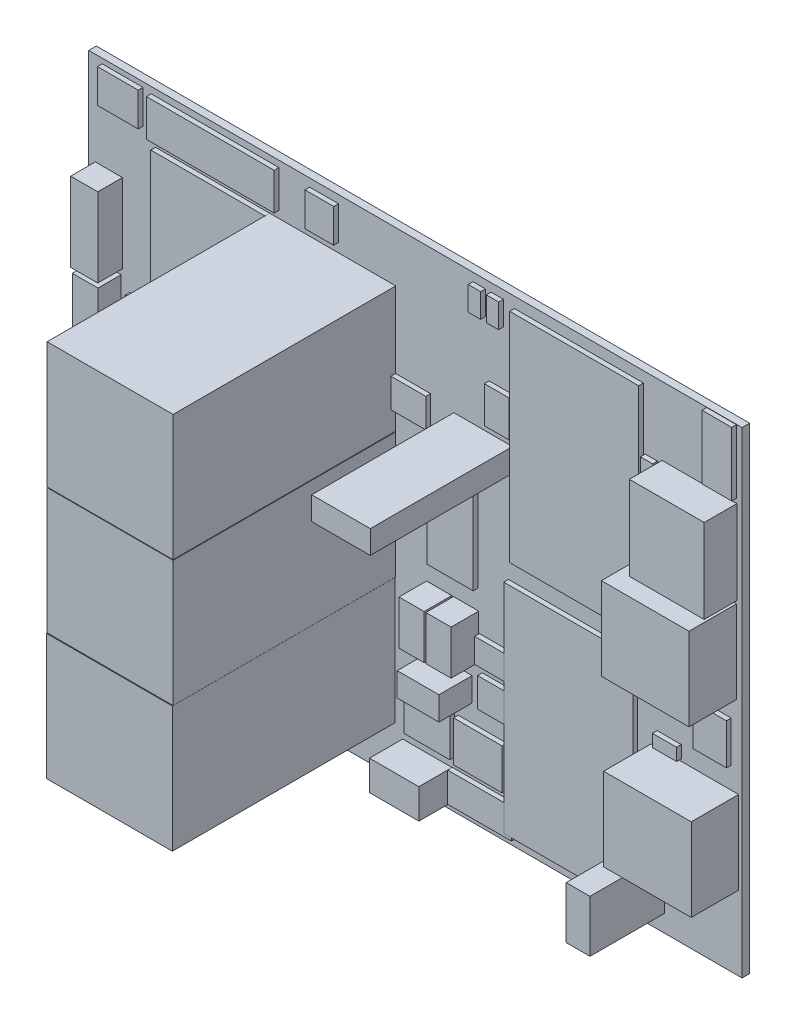
SolidWorks part; units mm, degrees
ref_plane "Plan de face" through (0, 0, 0) normal (0, 0, 1) x (1, 0, 0)
ref_plane "Plan de dessus" through (0, 0, 0) normal (0, 1, 0) x (1, 0, 0)
ref_plane "Plan de droite" through (0, 0, 0) normal (1, 0, 0) x (0, 0, -1)
sketch "Esquisse1" plane through (0, 0, 0) normal (0, 0, 1) x (1, 0, 0)
  line L0 (-2.0638, -0.1588) -> (135.87, -0.1588)
  line L1 (135.87, -0.1588) -> (135.87, 100.4762)
  line L2 (135.87, 100.4762) -> (-2.0638, 100.4762)
  line L3 (-2.0638, 100.4762) -> (-2.0638, -0.1588)
extrude "BOARD" add sketch "Esquisse1" along normal blind 1.6 separate body
ref_plane "Plan1" through (0, 0, 1.6) normal (0, 0, 1) x (1, 0, 0)
sketch "Esquisse2" plane through (0, 0, 0) normal (0, 0, 1) x (1, 0, 0)
  line L0 (109.1238, 29.3513) -> (109.1238, 26.2112)
  line L1 (109.1238, 26.2112) -> (110.9038, 26.2112)
  line L2 (110.9038, 26.2112) -> (110.9038, 29.3513)
  line L3 (110.9038, 29.3513) -> (109.1238, 29.3513)
extrude "CAP_0805-1" add sketch "Esquisse2" against normal blind 1 separate body
sketch "Esquisse3" plane through (0, 0, 0) normal (0, 0, 1) x (1, 0, 0)
  line L0 (110.9038, 22.8775) -> (110.9038, 26.0175)
  line L1 (110.9038, 26.0175) -> (109.1238, 26.0175)
  line L2 (109.1238, 26.0175) -> (109.1238, 22.8775)
  line L3 (109.1238, 22.8775) -> (110.9038, 22.8775)
extrude "CAP_0805-2" add sketch "Esquisse3" against normal blind 1 separate body
sketch "Esquisse4" plane through (0, 0, 0) normal (0, 0, 1) x (1, 0, 0)
  line L0 (94.1562, 24.0337) -> (97.2962, 24.0337)
  line L1 (97.2962, 24.0337) -> (97.2962, 25.8137)
  line L2 (97.2962, 25.8137) -> (94.1562, 25.8137)
  line L3 (94.1562, 25.8137) -> (94.1562, 24.0337)
extrude "CAP_0805-3" add sketch "Esquisse4" against normal blind 1 separate body
sketch "Esquisse5" plane through (0, 0, 0) normal (0, 0, 1) x (1, 0, 0)
  line L0 (94.7913, 37.845) -> (97.9312, 37.845)
  line L1 (97.9312, 37.845) -> (97.9312, 39.625)
  line L2 (97.9312, 39.625) -> (94.7913, 39.625)
  line L3 (94.7913, 39.625) -> (94.7913, 37.845)
extrude "CAP_0805-4" add sketch "Esquisse5" against normal blind 1 separate body
sketch "Esquisse6" plane through (0, 0, 0) normal (0, 0, 1) x (1, 0, 0)
  line L0 (68.0479, 19.7784) -> (68.0479, 15.7816)
  line L1 (68.0479, 15.7816) -> (70.0393, 15.7816)
  line L2 (70.0393, 15.7816) -> (70.0393, 19.7784)
  line L3 (70.0393, 19.7784) -> (68.0479, 19.7784)
extrude "C0805-1" add sketch "Esquisse6" against normal blind 1 separate body
sketch "Esquisse7" plane through (0, 0, 0) normal (0, 0, 1) x (1, 0, 0)
  line L0 (68.0479, 14.3809) -> (68.0479, 10.3841)
  line L1 (68.0479, 10.3841) -> (70.0393, 10.3841)
  line L2 (70.0393, 10.3841) -> (70.0393, 14.3809)
  line L3 (70.0393, 14.3809) -> (68.0479, 14.3809)
extrude "C0805-2" add sketch "Esquisse7" against normal blind 1 separate body
sketch "Esquisse8" plane through (0, 0, 1.6) normal (0, 0, 1) x (1, 0, 0)
  line L0 (36.15, 63.1475) -> (62.75, 63.1475)
  line L1 (62.75, 63.1475) -> (62.75, 36.5975)
  line L2 (62.75, 36.5975) -> (36.15, 36.5975)
  line L3 (36.15, 36.5975) -> (36.15, 63.1475)
extrude "SLPX102M200C4P3_47.000000-1" add sketch "Esquisse8" along normal blind 47 separate body
sketch "Esquisse9" plane through (0, 0, 1.6) normal (0, 0, 1) x (1, 0, 0)
  line L0 (36.15, 89.8175) -> (62.75, 89.8175)
  line L1 (62.75, 89.8175) -> (62.75, 63.2675)
  line L2 (62.75, 63.2675) -> (36.15, 63.2675)
  line L3 (36.15, 63.2675) -> (36.15, 89.8175)
extrude "Board_Outline2" add sketch "Esquisse9" along normal blind 47 separate body
sketch "Esquisse10" plane through (0, 0, 1.6) normal (0, 0, 1) x (1, 0, 0)
  line L0 (62.5925, 9.8775) -> (35.9925, 9.8775)
  line L1 (35.9925, 9.8775) -> (35.9925, 36.4275)
  line L2 (35.9925, 36.4275) -> (62.5925, 36.4275)
  line L3 (62.5925, 36.4275) -> (62.5925, 9.8775)
extrude "SLPX102M200C4P3_47.000000-3" add sketch "Esquisse10" along normal blind 47 separate body
sketch "Esquisse11" plane through (0, 0, 1.6) normal (0, 0, 1) x (1, 0, 0)
  line L0 (-0.6375, 52.0425) -> (-0.6375, 62.8925)
  line L1 (-0.6375, 62.8925) -> (4.7875, 62.8925)
  line L2 (4.7875, 62.8925) -> (4.7875, 52.0425)
  line L3 (4.7875, 52.0425) -> (-0.6375, 52.0425)
extrude "TO254P490X1000X2143-3P_4.900000-1" add sketch "Esquisse11" along normal blind 4.9 separate body
sketch "Esquisse12" plane through (0, 0, 1.6) normal (0, 0, 1) x (1, 0, 0)
  line L0 (-0.955, 23.15) -> (-0.955, 34)
  line L1 (-0.955, 34) -> (4.47, 34)
  line L2 (4.47, 34) -> (4.47, 23.15)
  line L3 (4.47, 23.15) -> (-0.955, 23.15)
extrude "TO254P490X1000X2143-3P_4.900000-2" add sketch "Esquisse12" along normal blind 4.9 separate body
sketch "Esquisse13" plane through (0, 0, 0) normal (0, 0, 1) x (1, 0, 0)
  line L0 (79.5337, 11.8275) -> (85.8837, 11.8275)
  line L1 (85.8837, 11.8275) -> (85.8837, 15.4525)
  line L2 (85.8837, 15.4525) -> (79.5337, 15.4525)
  line L3 (79.5337, 15.4525) -> (79.5337, 11.8275)
extrude "SOP50P490X110-10N_1.100000-1" add sketch "Esquisse13" against normal blind 1.1 separate body
sketch "Esquisse14" plane through (0, 0, 1.6) normal (0, 0, 1) x (1, 0, 0)
  line L0 (80.4228, 29.9403) -> (80.4228, 35.0838)
  line L1 (80.4228, 35.0838) -> (88.1063, 35.0838)
  line L2 (88.1063, 35.0838) -> (88.1063, 29.9403)
  line L3 (88.1063, 29.9403) -> (80.4228, 29.9403)
extrude "AVRISP-1" add sketch "Esquisse14" along normal blind 1 separate body
sketch "Esquisse15" plane through (0, 0, 1.6) normal (0, 0, 1) x (1, 0, 0)
  line L0 (116.6438, 15.5438) -> (116.6438, 33.0337)
  line L1 (116.6438, 33.0337) -> (135.1438, 33.0337)
  line L2 (135.1438, 33.0337) -> (135.1438, 15.5438)
  line L3 (135.1438, 15.5438) -> (116.6438, 15.5438)
extrude "UJ2BH1TH_10.000000-1" add sketch "Esquisse15" along normal blind 10 separate body
sketch "Esquisse16" plane through (0, 0, 1.6) normal (0, 0, 1) x (1, 0, 0)
  line L0 (116.1675, 50.1513) -> (116.1675, 67.6412)
  line L1 (116.1675, 67.6412) -> (134.6675, 67.6412)
  line L2 (134.6675, 67.6412) -> (134.6675, 50.1513)
  line L3 (134.6675, 50.1513) -> (116.1675, 50.1513)
extrude "UJ2BH1TH_10.000000-2" add sketch "Esquisse16" along normal blind 10 separate body
sketch "Esquisse17" plane through (0, 0, 1.6) normal (0, 0, 1) x (1, 0, 0)
  line L0 (133.5663, 46.22) -> (133.5663, 37.6)
  line L1 (133.5663, 37.6) -> (126.4663, 37.6)
  line L2 (126.4663, 37.6) -> (126.4663, 46.22)
  line L3 (126.4663, 46.22) -> (133.5663, 46.22)
extrude "691210910003-1" add sketch "Esquisse17" along normal blind 1 separate body
sketch "Esquisse18" plane through (0, 0, 1.6) normal (0, 0, 1) x (1, 0, 0)
  line L0 (74.6387, 1.405) -> (64.2137, 1.405)
  line L1 (64.2137, 1.405) -> (64.2137, 7.705)
  line L2 (64.2137, 7.705) -> (74.6387, 7.705)
  line L3 (74.6387, 7.705) -> (74.6387, 1.405)
extrude "SHDR3W64P0X250_1X3_990X575X700_7.000000-1" add sketch "Esquisse18" along normal blind 7 separate body
sketch "Esquisse19" plane through (0, 0, 1.6) normal (0, 0, 1) x (1, 0, 0)
  line L0 (88.1913, 1.5275) -> (74.7313, 1.5275)
  line L1 (74.7313, 1.5275) -> (74.7313, 7.7775)
  line L2 (74.7313, 7.7775) -> (88.1913, 7.7775)
  line L3 (88.1913, 7.7775) -> (88.1913, 1.5275)
extrude "JST_B4B-XH-A_LF__SN_-1" add sketch "Esquisse19" along normal blind 1 separate body
sketch "Esquisse20" plane through (0, 0, 1.6) normal (0, 0, 1) x (1, 0, 0)
  line L0 (134.68, 100.415) -> (134.68, 86.955)
  line L1 (134.68, 86.955) -> (128.43, 86.955)
  line L2 (128.43, 86.955) -> (128.43, 100.415)
  line L3 (128.43, 100.415) -> (134.68, 100.415)
extrude "JST_B4B-XH-A_LF__SN_-2" add sketch "Esquisse20" along normal blind 1 separate body
sketch "Esquisse21" plane through (0, 0, 1.6) normal (0, 0, 1) x (1, 0, 0)
  line L0 (50.665, 91.7) -> (44.585, 91.7)
  line L1 (44.585, 91.7) -> (44.585, 98.8)
  line L2 (44.585, 98.8) -> (50.665, 98.8)
  line L3 (50.665, 98.8) -> (50.665, 91.7)
extrude "691210910002-1" add sketch "Esquisse21" along normal blind 1 separate body
sketch "Esquisse22" plane through (0, 0, 1.6) normal (0, 0, 1) x (1, 0, 0)
  line L0 (9.39, 92.335) -> (0.77, 92.335)
  line L1 (0.77, 92.335) -> (0.77, 99.435)
  line L2 (0.77, 99.435) -> (9.39, 99.435)
  line L3 (9.39, 99.435) -> (9.39, 92.335)
extrude "691210910003-2" add sketch "Esquisse22" along normal blind 1 separate body
sketch "Esquisse23" plane through (0, 0, 0) normal (0, 0, 1) x (1, 0, 0)
  line L0 (78.105, 98.8441) -> (52.6034, 98.8441)
  line L1 (52.6034, 98.8441) -> (52.6034, 93.5609)
  line L2 (52.6034, 93.5609) -> (78.105, 93.5609)
  line L3 (78.105, 93.5609) -> (78.105, 98.8441)
extrude "JTAG-20-1" add sketch "Esquisse23" against normal blind 1 separate body
sketch "Esquisse24" plane through (0, 0, 1.6) normal (0, 0, 1) x (1, 0, 0)
  line L0 (50.03, 1.2125) -> (43.95, 1.2125)
  line L1 (43.95, 1.2125) -> (43.95, 8.3125)
  line L2 (43.95, 8.3125) -> (50.03, 8.3125)
  line L3 (50.03, 8.3125) -> (50.03, 1.2125)
extrude "691210910002-2" add sketch "Esquisse24" along normal blind 1 separate body
sketch "Esquisse25" plane through (0, 0, 1.6) normal (0, 0, 1) x (1, 0, 0)
  line L0 (10.025, 0.895) -> (1.405, 0.895)
  line L1 (1.405, 0.895) -> (1.405, 7.995)
  line L2 (1.405, 7.995) -> (10.025, 7.995)
  line L3 (10.025, 7.995) -> (10.025, 0.895)
extrude "691210910003-3" add sketch "Esquisse25" along normal blind 1 separate body
sketch "Esquisse26" plane through (0, 0, 1.6) normal (0, 0, 1) x (1, 0, 0)
  line L0 (118.975, 68.29) -> (118.975, 86.03)
  line L1 (118.975, 86.03) -> (134.775, 86.03)
  line L2 (134.775, 86.03) -> (134.775, 68.29)
  line L3 (134.775, 68.29) -> (118.975, 68.29)
extrude "SS52100001_6.900000-1" add sketch "Esquisse26" along normal blind 6.9 separate body
sketch "Esquisse27" plane through (0, 0, 1.6) normal (0, 0, 1) x (1, 0, 0)
  line L0 (117.9512, 36.1125) -> (123.0312, 36.1125)
  line L1 (123.0312, 36.1125) -> (123.0312, 33.4962)
  line L2 (123.0312, 33.4962) -> (117.9512, 33.4962)
  line L3 (117.9512, 33.4962) -> (117.9512, 36.1125)
extrude "1X02-1" add sketch "Esquisse27" along normal blind 1 separate body
sketch "Esquisse28" plane through (0, 0, 1.6) normal (0, 0, 1) x (1, 0, 0)
  line L0 (118.9037, 49.4475) -> (123.9838, 49.4475)
  line L1 (123.9838, 49.4475) -> (123.9838, 46.8312)
  line L2 (123.9838, 46.8312) -> (118.9037, 46.8312)
  line L3 (118.9037, 46.8312) -> (118.9037, 49.4475)
extrude "1X02-2" add sketch "Esquisse28" along normal blind 1 separate body
sketch "Esquisse29" plane through (0, 0, 1.6) normal (0, 0, 1) x (1, 0, 0)
  line L0 (118.1862, 73.8188) -> (118.1862, 68.7387)
  line L1 (118.1862, 68.7387) -> (115.57, 68.7387)
  line L2 (115.57, 68.7387) -> (115.57, 73.8188)
  line L3 (115.57, 73.8188) -> (118.1862, 73.8188)
extrude "1X02-3" add sketch "Esquisse29" along normal blind 1 separate body
sketch "Esquisse30" plane through (0, 0, 1.6) normal (0, 0, 1) x (1, 0, 0)
  line L0 (87.63, 82.3087) -> (87.63, 74.6125)
  line L1 (87.63, 74.6125) -> (82.4738, 74.6125)
  line L2 (82.4738, 74.6125) -> (82.4738, 82.3087)
  line L3 (82.4738, 82.3087) -> (87.63, 82.3087)
extrude "2X03-1" add sketch "Esquisse30" along normal blind 1 separate body
sketch "Esquisse31" plane through (0, 0, 1.6) normal (0, 0, 1) x (1, 0, 0)
  line L0 (85.4837, 98.7425) -> (85.4837, 93.6625)
  line L1 (85.4837, 93.6625) -> (82.8675, 93.6625)
  line L2 (82.8675, 93.6625) -> (82.8675, 98.7425)
  line L3 (82.8675, 98.7425) -> (85.4837, 98.7425)
extrude "1X02-4" add sketch "Esquisse31" along normal blind 1 separate body
sketch "Esquisse32" plane through (0, 0, 1.6) normal (0, 0, 1) x (1, 0, 0)
  line L0 (81.6737, 98.7425) -> (81.6737, 93.6625)
  line L1 (81.6737, 93.6625) -> (79.0575, 93.6625)
  line L2 (79.0575, 93.6625) -> (79.0575, 98.7425)
  line L3 (79.0575, 98.7425) -> (81.6737, 98.7425)
extrude "1X02-5" add sketch "Esquisse32" along normal blind 1 separate body
sketch "Esquisse33" plane through (0, 0, 1.6) normal (0, 0, 1) x (1, 0, 0)
  line L0 (118.0275, 85.4075) -> (118.0275, 80.3275)
  line L1 (118.0275, 80.3275) -> (115.4113, 80.3275)
  line L2 (115.4113, 80.3275) -> (115.4113, 85.4075)
  line L3 (115.4113, 85.4075) -> (118.0275, 85.4075)
extrude "1X02-6" add sketch "Esquisse33" along normal blind 1 separate body
sketch "Esquisse34" plane through (0, 0, 1.6) normal (0, 0, 1) x (1, 0, 0)
  line L0 (113.792, 48.0695) -> (113.792, 2.1155)
  line L1 (113.792, 2.1155) -> (86.577, 2.1155)
  line L2 (86.577, 2.1155) -> (86.577, 48.0695)
  line L3 (86.577, 48.0695) -> (113.792, 48.0695)
extrude "IRM-10-1" add sketch "Esquisse34" along normal blind 1 separate body
sketch "Esquisse35" plane through (0, 0, 1.6) normal (0, 0, 1) x (1, 0, 0)
  line L0 (87.8205, 52.2605) -> (87.8205, 98.2145)
  line L1 (87.8205, 98.2145) -> (115.0355, 98.2145)
  line L2 (115.0355, 98.2145) -> (115.0355, 52.2605)
  line L3 (115.0355, 52.2605) -> (87.8205, 52.2605)
extrude "IRM-10-2" add sketch "Esquisse35" along normal blind 1 separate body
sketch "Esquisse36" plane through (0, 0, 1.6) normal (0, 0, 1) x (1, 0, 0)
  line L0 (74.9537, 29.7737) -> (74.9537, 39.1237)
  line L1 (74.9537, 39.1237) -> (80.2788, 39.1237)
  line L2 (80.2788, 39.1237) -> (80.2788, 29.7737)
  line L3 (80.2788, 29.7737) -> (74.9537, 29.7737)
extrude "DIP762W58P254L450H584Q4N_5.840000-1" add sketch "Esquisse36" along normal blind 5.84 separate body
sketch "Esquisse37" plane through (0, 0, 1.6) normal (0, 0, 1) x (1, 0, 0)
  line L0 (74.5887, 39.1237) -> (74.5887, 29.7737)
  line L1 (74.5887, 29.7737) -> (69.2637, 29.7737)
  line L2 (69.2637, 29.7737) -> (69.2637, 39.1238)
  line L3 (69.2637, 39.1238) -> (74.5887, 39.1237)
extrude "DIP762W58P254L450H584Q4N_5.840000-2" add sketch "Esquisse37" along normal blind 5.84 separate body
sketch "Esquisse38" plane through (0, 0, 1.6) normal (0, 0, 1) x (1, 0, 0)
  line L0 (-0.675, 64.1025) -> (-0.675, 80.7825)
  line L1 (-0.675, 80.7825) -> (5.06, 80.7825)
  line L2 (5.06, 80.7825) -> (5.06, 64.1025)
  line L3 (5.06, 64.1025) -> (-0.675, 64.1025)
extrude "TO545P521X1594X2566-3P_5.210000-1" add sketch "Esquisse38" along normal blind 5.21 separate body
sketch "Esquisse39" plane through (0, 0, 1.6) normal (0, 0, 1) x (1, 0, 0)
  line L0 (14.3775, 55.1625) -> (21.3825, 55.1625)
  line L1 (21.3825, 55.1625) -> (21.3825, 50.8825)
  line L2 (21.3825, 50.8825) -> (14.3775, 50.8825)
  line L3 (14.3775, 50.8825) -> (14.3775, 55.1625)
extrude "ZTX458_4.010000-1" add sketch "Esquisse39" along normal blind 4.01 separate body
sketch "Esquisse40" plane through (0, 0, 1.6) normal (0, 0, 1) x (1, 0, 0)
  line L0 (14.3775, 49.13) -> (21.3825, 49.13)
  line L1 (21.3825, 49.13) -> (21.3825, 44.85)
  line L2 (21.3825, 44.85) -> (14.3775, 44.85)
  line L3 (14.3775, 44.85) -> (14.3775, 49.13)
extrude "ZTX458_4.010000-2" add sketch "Esquisse40" along normal blind 4.01 separate body
sketch "Esquisse41" plane through (0, 0, 1.6) normal (0, 0, 1) x (1, 0, 0)
  line L0 (-0.805, 10.27) -> (-0.805, 21.48)
  line L1 (-0.805, 21.48) -> (4.55, 21.48)
  line L2 (4.55, 21.48) -> (4.55, 10.27)
  line L3 (4.55, 10.27) -> (-0.805, 10.27)
extrude "TO254P483X1028X1700-3P_4.830000-1" add sketch "Esquisse41" along normal blind 4.83 separate body
sketch "Esquisse42" plane through (0, 0, 0) normal (0, 0, 1) x (1, 0, 0)
  line L0 (110.9968, 14.537) -> (110.9968, 18.483)
  line L1 (110.9968, 18.483) -> (109.0307, 18.483)
  line L2 (109.0307, 18.483) -> (109.0307, 14.537)
  line L3 (109.0307, 14.537) -> (110.9968, 14.537)
extrude "R0805-1" add sketch "Esquisse42" against normal blind 1 separate body
sketch "Esquisse43" plane through (0, 0, 0) normal (0, 0, 1) x (1, 0, 0)
  line L0 (109.0307, 14.1968) -> (109.0307, 10.2508)
  line L1 (109.0307, 10.2508) -> (110.9968, 10.2508)
  line L2 (110.9968, 10.2508) -> (110.9968, 14.1968)
  line L3 (110.9968, 14.1968) -> (109.0307, 14.1968)
extrude "R0805-2" add sketch "Esquisse43" against normal blind 1 separate body
sketch "Esquisse44" plane through (0, 0, 0) normal (0, 0, 1) x (1, 0, 0)
  line L0 (118.5557, 12.2918) -> (118.5557, 8.3457)
  line L1 (118.5557, 8.3457) -> (120.5217, 8.3457)
  line L2 (120.5217, 8.3457) -> (120.5217, 12.2918)
  line L3 (120.5217, 12.2918) -> (118.5557, 12.2918)
extrude "R0805-3" add sketch "Esquisse44" against normal blind 1 separate body
sketch "Esquisse45" plane through (0, 0, 0) normal (0, 0, 1) x (1, 0, 0)
  line L0 (72.6167, 8.2855) -> (68.6707, 8.2855)
  line L1 (68.6707, 8.2855) -> (68.6707, 6.3195)
  line L2 (68.6707, 6.3195) -> (72.6167, 6.3195)
  line L3 (72.6167, 6.3195) -> (72.6167, 8.2855)
extrude "R0805-4" add sketch "Esquisse45" against normal blind 1 separate body
sketch "Esquisse46" plane through (0, 0, 0) normal (0, 0, 1) x (1, 0, 0)
  line L0 (122.7443, 8.3457) -> (122.7443, 12.2918)
  line L1 (122.7443, 12.2918) -> (120.7782, 12.2918)
  line L2 (120.7782, 12.2918) -> (120.7782, 8.3457)
  line L3 (120.7782, 8.3457) -> (122.7443, 8.3457)
extrude "R0805-5" add sketch "Esquisse46" against normal blind 1 separate body
sketch "Esquisse47" plane through (0, 0, 0) normal (0, 0, 1) x (1, 0, 0)
  line L0 (122.7443, 4.2183) -> (122.7443, 8.1643)
  line L1 (122.7443, 8.1643) -> (120.7782, 8.1643)
  line L2 (120.7782, 8.1643) -> (120.7782, 4.2183)
  line L3 (120.7782, 4.2183) -> (122.7443, 4.2183)
extrude "R0805-6" add sketch "Esquisse47" against normal blind 1 separate body
sketch "Esquisse48" plane through (0, 0, 0) normal (0, 0, 1) x (1, 0, 0)
  line L0 (106.4907, 27.8492) -> (106.4907, 23.9032)
  line L1 (106.4907, 23.9032) -> (108.4567, 23.9032)
  line L2 (108.4567, 23.9032) -> (108.4567, 27.8492)
  line L3 (108.4567, 27.8492) -> (106.4907, 27.8492)
extrude "R0805-7" add sketch "Esquisse48" against normal blind 1 separate body
sketch "Esquisse49" plane through (0, 0, 0) normal (0, 0, 1) x (1, 0, 0)
  line L0 (104.2682, 27.8492) -> (104.2682, 23.9032)
  line L1 (104.2682, 23.9032) -> (106.2343, 23.9032)
  line L2 (106.2343, 23.9032) -> (106.2343, 27.8492)
  line L3 (106.2343, 27.8492) -> (104.2682, 27.8492)
extrude "R0805-8" add sketch "Esquisse49" against normal blind 1 separate body
sketch "Esquisse50" plane through (0, 0, 0) normal (0, 0, 1) x (1, 0, 0)
  line L0 (86.428, 23.843) -> (82.482, 23.843)
  line L1 (82.482, 23.843) -> (82.482, 21.877)
  line L2 (82.482, 21.877) -> (86.428, 21.877)
  line L3 (86.428, 21.877) -> (86.428, 23.843)
extrude "R0805-9" add sketch "Esquisse50" against normal blind 1 separate body
sketch "Esquisse51" plane through (0, 0, 0) normal (0, 0, 1) x (1, 0, 0)
  line L0 (76.3282, 15.6255) -> (76.3282, 11.6795)
  line L1 (76.3282, 11.6795) -> (78.2943, 11.6795)
  line L2 (78.2943, 11.6795) -> (78.2943, 15.6255)
  line L3 (78.2943, 15.6255) -> (76.3282, 15.6255)
extrude "R0805-10" add sketch "Esquisse51" against normal blind 1 separate body
sketch "Esquisse52" plane through (0, 0, 0) normal (0, 0, 1) x (1, 0, 0)
  line L0 (70.772, 19.753) -> (70.772, 15.807)
  line L1 (70.772, 15.807) -> (72.738, 15.807)
  line L2 (72.738, 15.807) -> (72.738, 19.753)
  line L3 (72.738, 19.753) -> (70.772, 19.753)
extrude "R0805-11" add sketch "Esquisse52" against normal blind 1 separate body
sketch "Esquisse53" plane through (0, 0, 0) normal (0, 0, 1) x (1, 0, 0)
  line L0 (70.6132, 14.3555) -> (70.6132, 10.4095)
  line L1 (70.6132, 10.4095) -> (72.5793, 10.4095)
  line L2 (72.5793, 10.4095) -> (72.5793, 14.3555)
  line L3 (72.5793, 14.3555) -> (70.6132, 14.3555)
extrude "R0805-12" add sketch "Esquisse53" against normal blind 1 separate body
sketch "Esquisse54" plane through (0, 0, 0) normal (0, 0, 1) x (1, 0, 0)
  line L0 (74.3255, 45.017) -> (74.3255, 48.963)
  line L1 (74.3255, 48.963) -> (72.3595, 48.963)
  line L2 (72.3595, 48.963) -> (72.3595, 45.017)
  line L3 (72.3595, 45.017) -> (74.3255, 45.017)
extrude "R0805-13" add sketch "Esquisse54" against normal blind 1 separate body
sketch "Esquisse55" plane through (0, 0, 0) normal (0, 0, 1) x (1, 0, 0)
  line L0 (75.3383, 27.4333) -> (79.2843, 27.4333)
  line L1 (79.2843, 27.4333) -> (79.2843, 29.3993)
  line L2 (79.2843, 29.3993) -> (75.3383, 29.3993)
  line L3 (75.3383, 29.3993) -> (75.3383, 27.4333)
extrude "R0805-14" add sketch "Esquisse55" against normal blind 1 separate body
sketch "Esquisse56" plane through (0, 0, 0) normal (0, 0, 1) x (1, 0, 0)
  line L0 (68.232, 48.963) -> (68.232, 45.017)
  line L1 (68.232, 45.017) -> (70.198, 45.017)
  line L2 (70.198, 45.017) -> (70.198, 48.963)
  line L3 (70.198, 48.963) -> (68.232, 48.963)
extrude "R0805-15" add sketch "Esquisse56" against normal blind 1 separate body
sketch "Esquisse57" plane through (0, 0, 0) normal (0, 0, 1) x (1, 0, 0)
  line L0 (117.2482, 54.262) -> (121.1942, 54.262)
  line L1 (121.1942, 54.262) -> (121.1942, 56.228)
  line L2 (121.1942, 56.228) -> (117.2482, 56.228)
  line L3 (117.2482, 56.228) -> (117.2482, 54.262)
extrude "R0805-16" add sketch "Esquisse57" against normal blind 1 separate body
sketch "Esquisse58" plane through (0, 0, 0) normal (0, 0, 1) x (1, 0, 0)
  line L0 (74.3255, 49.7795) -> (74.3255, 53.7255)
  line L1 (74.3255, 53.7255) -> (72.3595, 53.7255)
  line L2 (72.3595, 53.7255) -> (72.3595, 49.7795)
  line L3 (72.3595, 49.7795) -> (74.3255, 49.7795)
extrude "R0805-17" add sketch "Esquisse58" against normal blind 1 separate body
sketch "Esquisse59" plane through (0, 0, 0) normal (0, 0, 1) x (1, 0, 0)
  line L0 (75.9733, 39.3395) -> (79.9193, 39.3395)
  line L1 (79.9193, 39.3395) -> (79.9193, 41.3055)
  line L2 (79.9193, 41.3055) -> (75.9733, 41.3055)
  line L3 (75.9733, 41.3055) -> (75.9733, 39.3395)
extrude "R0805-18" add sketch "Esquisse59" against normal blind 1 separate body
sketch "Esquisse60" plane through (0, 0, 0) normal (0, 0, 1) x (1, 0, 0)
  line L0 (68.232, 53.7255) -> (68.232, 49.7795)
  line L1 (68.232, 49.7795) -> (70.198, 49.7795)
  line L2 (70.198, 49.7795) -> (70.198, 53.7255)
  line L3 (70.198, 53.7255) -> (68.232, 53.7255)
extrude "R0805-19" add sketch "Esquisse60" against normal blind 1 separate body
sketch "Esquisse61" plane through (0, 0, 0) normal (0, 0, 1) x (1, 0, 0)
  line L0 (117.2482, 58.707) -> (121.1942, 58.707)
  line L1 (121.1942, 58.707) -> (121.1942, 60.673)
  line L2 (121.1942, 60.673) -> (117.2482, 60.673)
  line L3 (117.2482, 60.673) -> (117.2482, 58.707)
extrude "R0805-20" add sketch "Esquisse61" against normal blind 1 separate body
sketch "Esquisse62" plane through (0, 0, 0) normal (0, 0, 1) x (1, 0, 0)
  line L0 (74.2043, 41.4642) -> (70.2583, 41.4642)
  line L1 (70.2583, 41.4642) -> (70.2583, 39.4983)
  line L2 (70.2583, 39.4983) -> (74.2043, 39.4983)
  line L3 (74.2043, 39.4983) -> (74.2043, 41.4642)
extrude "R0805-21" add sketch "Esquisse62" against normal blind 1 separate body
sketch "Esquisse63" plane through (0, 0, 0) normal (0, 0, 1) x (1, 0, 0)
  line L0 (117.2482, 56.4845) -> (121.1942, 56.4845)
  line L1 (121.1942, 56.4845) -> (121.1942, 58.4505)
  line L2 (121.1942, 58.4505) -> (117.2482, 58.4505)
  line L3 (117.2482, 58.4505) -> (117.2482, 56.4845)
extrude "R0805-22" add sketch "Esquisse63" against normal blind 1 separate body
sketch "Esquisse64" plane through (0, 0, 0) normal (0, 0, 1) x (1, 0, 0)
  line L0 (72.3595, 61.3455) -> (72.3595, 57.3995)
  line L1 (72.3595, 57.3995) -> (74.3255, 57.3995)
  line L2 (74.3255, 57.3995) -> (74.3255, 61.3455)
  line L3 (74.3255, 61.3455) -> (72.3595, 61.3455)
extrude "R0805-23" add sketch "Esquisse64" against normal blind 1 separate body
sketch "Esquisse65" plane through (0, 0, 0) normal (0, 0, 1) x (1, 0, 0)
  line L0 (73.5692, 29.3993) -> (69.6232, 29.3993)
  line L1 (69.6232, 29.3993) -> (69.6232, 27.4333)
  line L2 (69.6232, 27.4333) -> (73.5692, 27.4333)
  line L3 (73.5692, 27.4333) -> (73.5692, 29.3993)
extrude "R0805-24" add sketch "Esquisse65" against normal blind 1 separate body
sketch "Esquisse66" plane through (0, 0, 0) normal (0, 0, 1) x (1, 0, 0)
  line L0 (68.232, 61.3455) -> (68.232, 57.3995)
  line L1 (68.232, 57.3995) -> (70.198, 57.3995)
  line L2 (70.198, 57.3995) -> (70.198, 61.3455)
  line L3 (70.198, 61.3455) -> (68.232, 61.3455)
extrude "R0805-25" add sketch "Esquisse66" against normal blind 1 separate body
sketch "Esquisse67" plane through (0, 0, 0) normal (0, 0, 1) x (1, 0, 0)
  line L0 (76.1695, 61.3455) -> (76.1695, 57.3995)
  line L1 (76.1695, 57.3995) -> (78.1355, 57.3995)
  line L2 (78.1355, 57.3995) -> (78.1355, 61.3455)
  line L3 (78.1355, 61.3455) -> (76.1695, 61.3455)
extrude "R0805-26" add sketch "Esquisse67" against normal blind 1 separate body
sketch "Esquisse68" plane through (0, 0, 0) normal (0, 0, 1) x (1, 0, 0)
  line L0 (80.297, 61.3455) -> (80.297, 57.3995)
  line L1 (80.297, 57.3995) -> (82.263, 57.3995)
  line L2 (82.263, 57.3995) -> (82.263, 61.3455)
  line L3 (82.263, 61.3455) -> (80.297, 61.3455)
extrude "R0805-27" add sketch "Esquisse68" against normal blind 1 separate body
sketch "Esquisse69" plane through (0, 0, 0) normal (0, 0, 1) x (1, 0, 0)
  line L0 (68.867, 67.5367) -> (68.867, 63.5907)
  line L1 (68.867, 63.5907) -> (70.833, 63.5907)
  line L2 (70.833, 63.5907) -> (70.833, 67.5367)
  line L3 (70.833, 67.5367) -> (68.867, 67.5367)
extrude "R0805-28" add sketch "Esquisse69" against normal blind 1 separate body
sketch "Esquisse70" plane through (0, 0, 0) normal (0, 0, 1) x (1, 0, 0)
  line L0 (78.1355, 45.017) -> (78.1355, 48.963)
  line L1 (78.1355, 48.963) -> (76.1695, 48.963)
  line L2 (76.1695, 48.963) -> (76.1695, 45.017)
  line L3 (76.1695, 45.017) -> (78.1355, 45.017)
extrude "R0805-29" add sketch "Esquisse70" against normal blind 1 separate body
sketch "Esquisse71" plane through (0, 0, 0) normal (0, 0, 1) x (1, 0, 0)
  line L0 (80.297, 48.963) -> (80.297, 45.017)
  line L1 (80.297, 45.017) -> (82.263, 45.017)
  line L2 (82.263, 45.017) -> (82.263, 48.963)
  line L3 (82.263, 48.963) -> (80.297, 48.963)
extrude "R0805-30" add sketch "Esquisse71" against normal blind 1 separate body
sketch "Esquisse72" plane through (0, 0, 0) normal (0, 0, 1) x (1, 0, 0)
  line L0 (82.263, 49.7795) -> (82.263, 53.7255)
  line L1 (82.263, 53.7255) -> (80.297, 53.7255)
  line L2 (80.297, 53.7255) -> (80.297, 49.7795)
  line L3 (80.297, 49.7795) -> (82.263, 49.7795)
extrude "R0805-31" add sketch "Esquisse72" against normal blind 1 separate body
sketch "Esquisse73" plane through (0, 0, 0) normal (0, 0, 1) x (1, 0, 0)
  line L0 (76.1695, 53.7255) -> (76.1695, 49.7795)
  line L1 (76.1695, 49.7795) -> (78.1355, 49.7795)
  line L2 (78.1355, 49.7795) -> (78.1355, 53.7255)
  line L3 (78.1355, 53.7255) -> (76.1695, 53.7255)
extrude "R0805-32" add sketch "Esquisse73" against normal blind 1 separate body
sketch "Esquisse74" plane through (0, 0, 0) normal (0, 0, 1) x (1, 0, 0)
  line L0 (68.6359, 87.2191) -> (68.6359, 91.2159)
  line L1 (68.6359, 91.2159) -> (66.6445, 91.2159)
  line L2 (66.6445, 91.2159) -> (66.6445, 87.2191)
  line L3 (66.6445, 87.2191) -> (68.6359, 87.2191)
extrude "M0805-1" add sketch "Esquisse74" against normal blind 1 separate body
sketch "Esquisse75" plane through (0, 0, 0) normal (0, 0, 1) x (1, 0, 0)
  line L0 (70.8584, 87.2191) -> (70.8584, 91.2159)
  line L1 (70.8584, 91.2159) -> (68.867, 91.2159)
  line L2 (68.867, 91.2159) -> (68.867, 87.2191)
  line L3 (68.867, 87.2191) -> (70.8584, 87.2191)
extrude "M0805-2" add sketch "Esquisse75" against normal blind 1 separate body
sketch "Esquisse76" plane through (0, 0, 0) normal (0, 0, 1) x (1, 0, 0)
  line L0 (73.0809, 87.2191) -> (73.0809, 91.2159)
  line L1 (73.0809, 91.2159) -> (71.0895, 91.2159)
  line L2 (71.0895, 91.2159) -> (71.0895, 87.2191)
  line L3 (71.0895, 87.2191) -> (73.0809, 87.2191)
extrude "M0805-3" add sketch "Esquisse76" against normal blind 1 separate body
sketch "Esquisse77" plane through (0, 0, 0) normal (0, 0, 1) x (1, 0, 0)
  line L0 (80.5891, 91.2159) -> (80.5891, 87.2191)
  line L1 (80.5891, 87.2191) -> (82.5805, 87.2191)
  line L2 (82.5805, 87.2191) -> (82.5805, 91.2159)
  line L3 (82.5805, 91.2159) -> (80.5891, 91.2159)
extrude "M0805-4" add sketch "Esquisse77" against normal blind 1 separate body
sketch "Esquisse78" plane through (0, 0, 0) normal (0, 0, 1) x (1, 0, 0)
  line L0 (82.8116, 91.2159) -> (82.8116, 87.2191)
  line L1 (82.8116, 87.2191) -> (84.803, 87.2191)
  line L2 (84.803, 87.2191) -> (84.803, 91.2159)
  line L3 (84.803, 91.2159) -> (82.8116, 91.2159)
extrude "M0805-5" add sketch "Esquisse78" against normal blind 1 separate body
sketch "Esquisse79" plane through (0, 0, 0) normal (0, 0, 1) x (1, 0, 0)
  line L0 (78.3666, 91.2159) -> (78.3666, 87.2191)
  line L1 (78.3666, 87.2191) -> (80.358, 87.2191)
  line L2 (80.358, 87.2191) -> (80.358, 91.2159)
  line L3 (80.358, 91.2159) -> (78.3666, 91.2159)
extrude "M0805-6" add sketch "Esquisse79" against normal blind 1 separate body
sketch "Esquisse80" plane through (0, 0, 0) normal (0, 0, 1) x (1, 0, 0)
  line L0 (73.4454, 91.2159) -> (73.4454, 87.2191)
  line L1 (73.4454, 87.2191) -> (75.4368, 87.2191)
  line L2 (75.4368, 87.2191) -> (75.4368, 91.2159)
  line L3 (75.4368, 91.2159) -> (73.4454, 91.2159)
extrude "M0805-7" add sketch "Esquisse80" against normal blind 1 separate body
sketch "Esquisse81" plane through (0, 0, 0) normal (0, 0, 1) x (1, 0, 0)
  line L0 (77.8434, 87.2191) -> (77.8434, 91.2159)
  line L1 (77.8434, 91.2159) -> (75.852, 91.2159)
  line L2 (75.852, 91.2159) -> (75.852, 87.2191)
  line L3 (75.852, 87.2191) -> (77.8434, 87.2191)
extrude "M0805-8" add sketch "Esquisse81" against normal blind 1 separate body
sketch "Esquisse82" plane through (0, 0, 0) normal (0, 0, 1) x (1, 0, 0)
  line L0 (75.1916, 67.5622) -> (75.1916, 63.5653)
  line L1 (75.1916, 63.5653) -> (77.183, 63.5654)
  line L2 (77.183, 63.5654) -> (77.183, 67.5622)
  line L3 (77.183, 67.5622) -> (75.1916, 67.5622)
extrude "M0805-9" add sketch "Esquisse82" against normal blind 1 separate body
sketch "Esquisse83" plane through (0, 0, 0) normal (0, 0, 1) x (1, 0, 0)
  line L0 (77.2554, 67.5622) -> (77.2554, 63.5653)
  line L1 (77.2554, 63.5653) -> (79.2468, 63.5654)
  line L2 (79.2468, 63.5654) -> (79.2468, 67.5622)
  line L3 (79.2468, 67.5622) -> (77.2554, 67.5622)
extrude "M0805-10" add sketch "Esquisse83" against normal blind 1 separate body
sketch "Esquisse84" plane through (0, 0, 0) normal (0, 0, 1) x (1, 0, 0)
  line L0 (71.0641, 67.5622) -> (71.0641, 63.5653)
  line L1 (71.0641, 63.5653) -> (73.0555, 63.5654)
  line L2 (73.0555, 63.5654) -> (73.0555, 67.5622)
  line L3 (73.0555, 67.5622) -> (71.0641, 67.5622)
extrude "M0805-11" add sketch "Esquisse84" against normal blind 1 separate body
sketch "Esquisse85" plane through (0, 0, 0) normal (0, 0, 1) x (1, 0, 0)
  line L0 (73.1279, 67.5622) -> (73.1279, 63.5653)
  line L1 (73.1279, 63.5653) -> (75.1193, 63.5654)
  line L2 (75.1193, 63.5654) -> (75.1193, 67.5622)
  line L3 (75.1193, 67.5622) -> (73.1279, 67.5622)
extrude "M0805-12" add sketch "Esquisse85" against normal blind 1 separate body
sketch "Esquisse86" plane through (0, 0, 1.6) normal (0, 0, 1) x (1, 0, 0)
  line L0 (11.1125, 99.125) -> (38.0875, 99.125)
  line L1 (38.0875, 99.125) -> (38.0875, 91.2988)
  line L2 (38.0875, 91.2988) -> (11.1125, 91.2988)
  line L3 (11.1125, 91.2988) -> (11.1125, 99.125)
extrude "RS05_69-70-1" add sketch "Esquisse86" along normal blind 1 separate body
sketch "Esquisse87" plane through (0, 0, 1.6) normal (0, 0, 1) x (1, 0, 0)
  line L0 (11.7475, 8.6375) -> (38.7225, 8.6375)
  line L1 (38.7225, 8.6375) -> (38.7225, 0.8113)
  line L2 (38.7225, 0.8113) -> (11.7475, 0.8113)
  line L3 (11.7475, 0.8113) -> (11.7475, 8.6375)
extrude "RS05_69-70-2" add sketch "Esquisse87" along normal blind 1 separate body
sketch "Esquisse88" plane through (0, 0, 0) normal (0, 0, 1) x (1, 0, 0)
  line L0 (8.636, 68.2625) -> (8.636, 76.1365)
  line L1 (8.636, 76.1365) -> (6.604, 76.1365)
  line L2 (6.604, 76.1365) -> (6.604, 68.2625)
  line L3 (6.604, 68.2625) -> (8.636, 68.2625)
extrude "0204_7-1" add sketch "Esquisse88" against normal blind 1 separate body
sketch "Esquisse89" plane through (0, 0, 1.6) normal (0, 0, 1) x (1, 0, 0)
  line L0 (6.604, 52.705) -> (6.604, 60.579)
  line L1 (6.604, 60.579) -> (8.636, 60.579)
  line L2 (8.636, 60.579) -> (8.636, 52.705)
  line L3 (8.636, 52.705) -> (6.604, 52.705)
extrude "0204_7-2" add sketch "Esquisse89" along normal blind 1 separate body
sketch "Esquisse90" plane through (0, 0, 1.6) normal (0, 0, 1) x (1, 0, 0)
  line L0 (8.636, 19.3675) -> (8.636, 11.4935)
  line L1 (8.636, 11.4935) -> (6.604, 11.4935)
  line L2 (6.604, 11.4935) -> (6.604, 19.3675)
  line L3 (6.604, 19.3675) -> (8.636, 19.3675)
extrude "0204_7-3" add sketch "Esquisse90" along normal blind 1 separate body
sketch "Esquisse91" plane through (0, 0, 1.6) normal (0, 0, 1) x (1, 0, 0)
  line L0 (25.4, 50.8635) -> (33.274, 50.8635)
  line L1 (33.274, 50.8635) -> (33.274, 48.8315)
  line L2 (33.274, 48.8315) -> (25.4, 48.8315)
  line L3 (25.4, 48.8315) -> (25.4, 50.8635)
extrude "0204_7-4" add sketch "Esquisse91" along normal blind 1 separate body
sketch "Esquisse92" plane through (0, 0, 1.6) normal (0, 0, 1) x (1, 0, 0)
  line L0 (8.636, 40.64) -> (8.636, 32.766)
  line L1 (8.636, 32.766) -> (6.604, 32.766)
  line L2 (6.604, 32.766) -> (6.604, 40.64)
  line L3 (6.604, 40.64) -> (8.636, 40.64)
extrude "0204_7-5" add sketch "Esquisse92" along normal blind 1 separate body
sketch "Esquisse93" plane through (0, 0, 1.6) normal (0, 0, 1) x (1, 0, 0)
  line L0 (25.4, 53.4035) -> (33.274, 53.4035)
  line L1 (33.274, 53.4035) -> (33.274, 51.3715)
  line L2 (33.274, 51.3715) -> (25.4, 51.3715)
  line L3 (25.4, 51.3715) -> (25.4, 53.4035)
extrude "0204_7-6" add sketch "Esquisse93" along normal blind 1 separate body
sketch "Esquisse94" plane through (0, 0, 1.6) normal (0, 0, 1) x (1, 0, 0)
  line L0 (81.0375, 28.222) -> (88.66, 28.222)
  line L1 (88.66, 28.222) -> (88.66, 22.0825)
  line L2 (88.66, 22.0825) -> (81.0375, 22.0825)
  line L3 (81.0375, 22.0825) -> (81.0375, 28.222)
extrude "1825910-6-1" add sketch "Esquisse94" along normal blind 1 separate body
sketch "Esquisse95" plane through (0, 0, 1.6) normal (0, 0, 1) x (1, 0, 0)
  line L0 (70.0925, 67.663) -> (62.47, 67.663)
  line L1 (62.47, 67.663) -> (62.47, 73.8025)
  line L2 (62.47, 73.8025) -> (70.0925, 73.8025)
  line L3 (70.0925, 73.8025) -> (70.0925, 67.663)
extrude "1825910-6-2" add sketch "Esquisse95" along normal blind 1 separate body
sketch "Esquisse96" plane through (0, 0, 0) normal (0, 0, 1) x (1, 0, 0)
  line L0 (119.3113, 19.5645) -> (119.3113, 30.1999)
  line L1 (119.3113, 30.1999) -> (111.452, 30.1999)
  line L2 (111.452, 30.1999) -> (111.452, 19.5645)
  line L3 (111.452, 19.5645) -> (119.3113, 19.5645)
extrude "SSOP28DB-1" add sketch "Esquisse96" against normal blind 1 separate body
sketch "Esquisse97" plane through (0, 0, 1.6) normal (0, 0, 1) x (1, 0, 0)
  line L0 (114.4887, 14.4662) -> (119.5088, 14.4662)
  line L1 (119.5088, 14.4662) -> (119.5088, 3.4912)
  line L2 (119.5088, 3.4912) -> (114.4887, 3.4912)
  line L3 (114.4887, 3.4912) -> (114.4887, 14.4662)
extrude "ON_SEMI_LM317BTG_0_15.750000-1" add sketch "Esquisse97" along normal blind 15.75 separate body
sketch "Esquisse98" plane through (0, 0, 0) normal (0, 0, 1) x (1, 0, 0)
  line L0 (89.0213, 15.3587) -> (98.6213, 15.3587)
  line L1 (98.6213, 15.3587) -> (98.6213, 23.0587)
  line L2 (98.6213, 23.0587) -> (89.0213, 23.0587)
  line L3 (89.0213, 23.0587) -> (89.0213, 15.3587)
extrude "NATIONAL_SEMICONDUCTOR_LM1117IMPX-3_3-NOPB_2-1" add sketch "Esquisse98" against normal blind 1 separate body
sketch "Esquisse99" plane through (0, 0, 0) normal (0, 0, 1) x (1, 0, 0)
  line L0 (91.2438, 65.8413) -> (100.8438, 65.8413)
  line L1 (100.8438, 65.8413) -> (100.8438, 73.5412)
  line L2 (100.8438, 73.5412) -> (91.2438, 73.5412)
  line L3 (91.2438, 73.5412) -> (91.2438, 65.8413)
extrude "NATIONAL_SEMICONDUCTOR_LM1117IMPX-3_3-NOPB_2-2" add sketch "Esquisse99" against normal blind 1 separate body
sketch "Esquisse100" plane through (0, 0, 0) normal (0, 0, 1) x (1, 0, 0)
  line L0 (101.8612, 26.7263) -> (101.8612, 37.7263)
  line L1 (101.8612, 37.7263) -> (90.8612, 37.7263)
  line L2 (90.8612, 37.7263) -> (90.8612, 26.7263)
  line L3 (90.8612, 26.7263) -> (101.8612, 26.7263)
extrude "QFP80P900X900X120-32N-1" add sketch "Esquisse100" against normal blind 1 separate body
sketch "Esquisse101" plane through (0, 0, 1.6) normal (0, 0, 1) x (1, 0, 0)
  line L0 (65.4763, 20.6) -> (75.1762, 20.6)
  line L1 (75.1762, 20.6) -> (75.1762, 9.89)
  line L2 (75.1762, 9.89) -> (65.4763, 9.89)
  line L3 (65.4763, 9.89) -> (65.4763, 20.6)
extrude "TEXAS_INSTRUMENTS_TLC2262CP_0-1" add sketch "Esquisse101" along normal blind 1 separate body
sketch "Esquisse102" plane through (0, 0, 1.6) normal (0, 0, 1) x (1, 0, 0)
  line L0 (75.9651, 9.3599) -> (75.9651, 17.9451)
  line L1 (75.9651, 17.9451) -> (86.2013, 17.9451)
  line L2 (86.2013, 17.9451) -> (86.2013, 9.3599)
  line L3 (86.2013, 9.3599) -> (75.9651, 9.3599)
extrude "DIP254P762X533-8-1" add sketch "Esquisse102" along normal blind 1 separate body
sketch "Esquisse103" plane through (0, 0, 1.6) normal (0, 0, 1) x (1, 0, 0)
  line L0 (70.3975, 63.44) -> (80.0975, 63.44)
  line L1 (80.0975, 63.44) -> (80.0975, 43.24)
  line L2 (80.0975, 43.24) -> (70.3975, 43.24)
  line L3 (70.3975, 43.24) -> (70.3975, 63.44)
extrude "TEXAS_INSTRUMENTS_TLC2264CN_0-1" add sketch "Esquisse103" along normal blind 1 separate body
sketch "Esquisse104" plane through (0, 0, 1.6) normal (0, 0, 1) x (1, 0, 0)
  line L0 (12.03, 55.6075) -> (12.03, 89.8075)
  line L1 (12.03, 89.8075) -> (36.13, 89.8075)
  line L2 (36.13, 89.8075) -> (36.13, 55.6075)
  line L3 (36.13, 55.6075) -> (12.03, 55.6075)
extrude "SC-10-30J-1" add sketch "Esquisse104" along normal blind 1 separate body
sketch "Esquisse105" plane through (0, 0, 1.6) normal (0, 0, 1) x (1, 0, 0)
  line L0 (35.2775, 44.0875) -> (35.2775, 9.8875)
  line L1 (35.2775, 9.8875) -> (11.1775, 9.8875)
  line L2 (11.1775, 9.8875) -> (11.1775, 44.0875)
  line L3 (11.1775, 44.0875) -> (35.2775, 44.0875)
extrude "SC-10-30J-2" add sketch "Esquisse105" along normal blind 1 separate body
sketch "Esquisse106" plane through (0, 0, 0) normal (0, 0, 1) x (1, 0, 0)
  line L0 (79.9812, 72.1725) -> (79.9812, 83.6325)
  line L1 (79.9812, 83.6325) -> (69.5613, 83.6325)
  line L2 (69.5613, 83.6325) -> (69.5613, 72.1725)
  line L3 (69.5613, 72.1725) -> (79.9812, 72.1725)
extrude "QFP50P900X900X160-48N-1" add sketch "Esquisse106" against normal blind 1 separate body
sketch "Esquisse107" plane through (0, 0, 1.6) normal (0, 0, 1) x (1, 0, 0)
  line L0 (75.0225, 72.7772) -> (87.3985, 72.7772)
  line L1 (87.3985, 72.7772) -> (87.3985, 67.8753)
  line L2 (87.3985, 67.8753) -> (75.0225, 67.8753)
  line L3 (75.0225, 67.8753) -> (75.0225, 72.7772)
extrude "FOX_ELECTRONICS_FOXSLF-080-20_0_30.020000-1" add sketch "Esquisse107" along normal blind 30.02 separate body
sketch "Esquisse108" plane through (0, 0, 1.6) normal (0, 0, 1) x (1, 0, 0)
  line L0 (70.0502, 26.63) -> (78.8762, 26.63)
  line L1 (78.8762, 26.63) -> (78.8762, 21.63)
  line L2 (78.8762, 21.63) -> (70.0502, 21.63)
  line L3 (70.0502, 21.63) -> (70.0502, 26.63)
extrude "CSTLS16M0X53ZA0_7.000000-1" add sketch "Esquisse108" along normal blind 7 separate body
